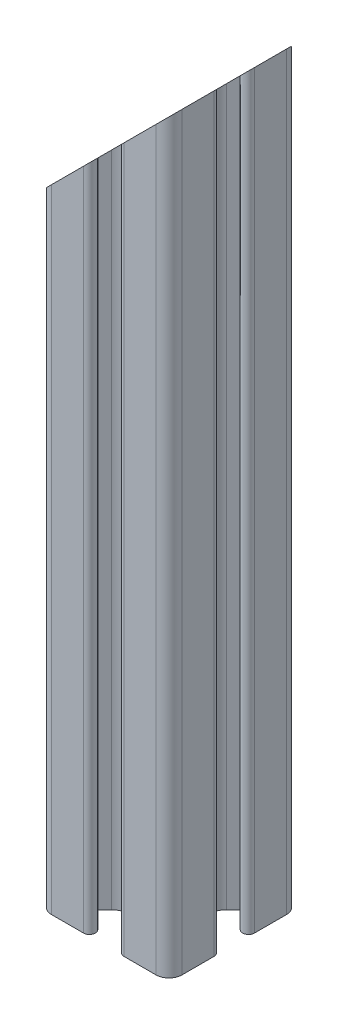
SolidWorks part; units mm, degrees
ref_plane "前视基准面" through (0, 0, 0) normal (0, 0, 1) x (1, 0, 0)
ref_plane "上视基准面" through (0, 0, 0) normal (0, 1, 0) x (1, 0, 0)
ref_plane "右视基准面" through (0, 0, 0) normal (1, 0, 0) x (0, 0, -1)
sketch "草图1" plane through (0, 0, 0) normal (0, 1, 0) x (1, 0, 0)
  line L0 (-1.0428, -10.0859) -> (3.8572, -10.0859)
  line L1 (1.0762, -11.8859) -> (3.8572, -11.8859)
  line L2 (2.8854, -15.3072) -> (0.7226, -13.1443)
  line L3 (2.1786, -16.0141) -> (0.0157, -13.8512)
  line L4 (-3.0428, -12.0859) -> (-3.0428, -16.9859)
  line L5 (-1.2428, -14.2048) -> (-1.2428, -16.9859)
  line L6 (-0.7428, -13.7048) -> (-0.3378, -13.7048)
  line L7 (0.5762, -12.3859) -> (0.5762, -12.7908)
  line L8 (-1.0428, -30.0859) -> (3.8572, -30.0859)
  line L9 (1.0762, -28.2859) -> (3.8572, -28.2859)
  line L10 (2.8854, -24.8645) -> (0.7226, -27.0274)
  line L11 (2.1786, -24.1577) -> (0.0157, -26.3205)
  line L12 (-3.0428, -28.0859) -> (-3.0428, -23.1859)
  line L13 (-1.2428, -25.9669) -> (-1.2428, -23.1859)
  line L14 (-0.7428, -26.4669) -> (-0.3378, -26.4669)
  line L15 (0.5762, -27.7859) -> (0.5762, -27.3809)
  line L16 (14.9572, -10.0859) -> (10.0572, -10.0859)
  line L17 (12.8383, -11.8859) -> (10.0572, -11.8859)
  line L18 (11.029, -15.3072) -> (13.1919, -13.1443)
  line L19 (11.7359, -16.0141) -> (13.8988, -13.8512)
  line L20 (16.9572, -12.0859) -> (16.9572, -16.9859)
  line L21 (15.1572, -14.2048) -> (15.1572, -16.9859)
  line L22 (14.6572, -13.7048) -> (14.2523, -13.7048)
  line L23 (13.3383, -12.3859) -> (13.3383, -12.7908)
  line L24 (14.9572, -30.0859) -> (10.0572, -30.0859)
  line L25 (12.8383, -28.2859) -> (10.0572, -28.2859)
  line L26 (11.029, -24.8645) -> (13.1919, -27.0274)
  line L27 (11.7359, -24.1577) -> (13.8988, -26.3205)
  line L28 (16.9572, -28.0859) -> (16.9572, -23.1859)
  line L29 (15.1572, -25.9669) -> (15.1572, -23.1859)
  line L30 (14.6572, -26.4669) -> (14.2523, -26.4669)
  line L31 (13.3383, -27.7859) -> (13.3383, -27.3809)
  line L32 (5.0068, -16.1859) -> (8.9077, -16.1859)
  line L33 (10.8572, -18.1354) -> (10.8572, -22.0363)
  line L34 (3.0572, -18.1354) -> (3.0572, -22.0363)
  line L35 (5.0068, -23.9859) -> (8.9077, -23.9859)
  circle A0 centre (6.9572, -20.0859) radius 2.5
  arc A1 (2.8854, -15.3072) -> (5.0068, -16.1859) centre (5.0068, -13.1859) ccw
  arc A2 (3.0572, -18.1354) -> (2.1786, -16.0141) centre (0.0572, -18.1354) ccw
  arc A3 (3.8572, -11.8859) -> (3.8572, -10.0859) centre (3.8572, -10.9859) ccw
  arc A4 (0.5762, -12.7908) -> (0.7226, -13.1443) centre (1.0762, -12.7908) ccw
  arc A5 (0.0157, -13.8512) -> (-0.3378, -13.7048) centre (-0.3378, -14.2048) ccw
  arc A6 (-3.0428, -16.9859) -> (-1.2428, -16.9859) centre (-2.1428, -16.9859) ccw
  arc A7 (-1.0428, -10.0859) -> (-3.0428, -12.0859) centre (-1.0428, -12.0859) ccw
  arc A8 (-0.7428, -13.7048) -> (-1.2428, -14.2048) centre (-0.7428, -14.2048) ccw
  arc A9 (1.0762, -11.8859) -> (0.5762, -12.3859) centre (1.0762, -12.3859) ccw
  arc A10 (5.0068, -23.9859) -> (2.8854, -24.8645) centre (5.0068, -26.9859) ccw
  arc A11 (2.1786, -24.1577) -> (3.0572, -22.0363) centre (0.0572, -22.0363) ccw
  arc A12 (3.8572, -30.0859) -> (3.8572, -28.2859) centre (3.8572, -29.1859) ccw
  arc A13 (0.7226, -27.0274) -> (0.5762, -27.3809) centre (1.0762, -27.3809) ccw
  arc A14 (-0.3378, -26.4669) -> (0.0157, -26.3205) centre (-0.3378, -25.9669) ccw
  arc A15 (-1.2428, -23.1859) -> (-3.0428, -23.1859) centre (-2.1428, -23.1859) ccw
  arc A16 (-3.0428, -28.0859) -> (-1.0428, -30.0859) centre (-1.0428, -28.0859) ccw
  arc A17 (-1.2428, -25.9669) -> (-0.7428, -26.4669) centre (-0.7428, -25.9669) ccw
  arc A18 (0.5762, -27.7859) -> (1.0762, -28.2859) centre (1.0762, -27.7859) ccw
  arc A19 (8.9077, -16.1859) -> (11.029, -15.3072) centre (8.9077, -13.1859) ccw
  arc A20 (11.7359, -16.0141) -> (10.8572, -18.1354) centre (13.8572, -18.1354) ccw
  arc A21 (10.0572, -10.0859) -> (10.0572, -11.8859) centre (10.0572, -10.9859) ccw
  arc A22 (13.1919, -13.1443) -> (13.3383, -12.7908) centre (12.8383, -12.7908) ccw
  arc A23 (14.2523, -13.7048) -> (13.8988, -13.8512) centre (14.2523, -14.2048) ccw
  arc A24 (15.1572, -16.9859) -> (16.9572, -16.9859) centre (16.0572, -16.9859) ccw
  arc A25 (16.9572, -12.0859) -> (14.9572, -10.0859) centre (14.9572, -12.0859) ccw
  arc A26 (15.1572, -14.2048) -> (14.6572, -13.7048) centre (14.6572, -14.2048) ccw
  arc A27 (13.3383, -12.3859) -> (12.8383, -11.8859) centre (12.8383, -12.3859) ccw
  arc A28 (11.029, -24.8645) -> (8.9077, -23.9859) centre (8.9077, -26.9859) ccw
  arc A29 (10.8572, -22.0363) -> (11.7359, -24.1577) centre (13.8572, -22.0363) ccw
  arc A30 (10.0572, -28.2859) -> (10.0572, -30.0859) centre (10.0572, -29.1859) ccw
  arc A31 (13.3383, -27.3809) -> (13.1919, -27.0274) centre (12.8383, -27.3809) ccw
  arc A32 (13.8988, -26.3205) -> (14.2523, -26.4669) centre (14.2523, -25.9669) ccw
  arc A33 (16.9572, -23.1859) -> (15.1572, -23.1859) centre (16.0572, -23.1859) ccw
  arc A34 (14.9572, -30.0859) -> (16.9572, -28.0859) centre (14.9572, -28.0859) ccw
  arc A35 (14.6572, -26.4669) -> (15.1572, -25.9669) centre (14.6572, -25.9669) ccw
  arc A36 (12.8383, -28.2859) -> (13.3383, -27.7859) centre (12.8383, -27.7859) ccw
extrude "凸台-拉伸1" add sketch "草图1" along normal blind 115 contours L33 A29 L27 A32 L30 A35 L29 A33 L28 A34 L24 A30 L25 A36 L31 A31 L26 A28 L35 A10 L10 A13 L15 A18 L9 A12 L8 A16 L12 A15 L13 A17 L14 A14 L11 A11 L34 A2 L3 A5 L6 A8 L5 A6 L4 A7 L0 A3 L1 A9 L7 A4 L2 A1 L32 A19 L18 A22 L23 A27 L17 A21 L16 A25 L20 A24 L21 A26 L22 A23 L19 A20
sketch "草图2" plane through (0, 0, 30.0859) normal (0, 0, 1) x (1, 0, 0)
  line L0 (16.9572, 115) -> (-3.0428, 95)
  line L1 (-3.0428, 115) -> (-3.0428, 0) construction
  line L2 (5.0068, 115) -> (8.9077, 115) construction
  line L3 (-3.0428, 95) -> (-3.0428, 115)
  line L4 (-3.0428, 115) -> (16.9572, 115)
  dimension "D1" = 45
extrude "切除-拉伸1" cut sketch "草图2" against normal through all
